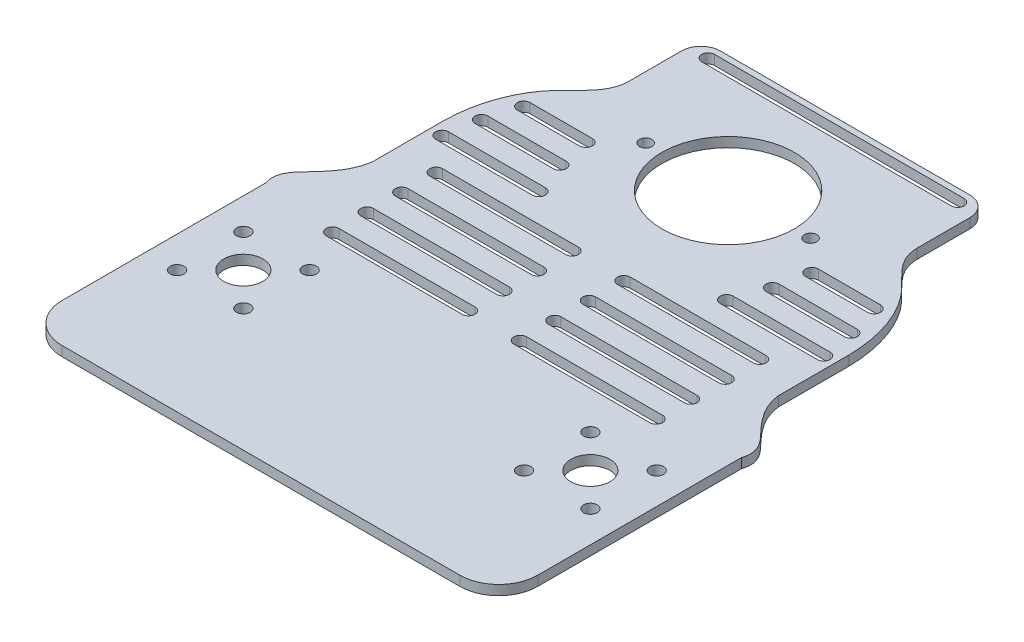
SolidWorks part; units mm, degrees
ref_plane "前视基准面" through (0, 0, 0) normal (0, 0, 1) x (1, 0, 0)
ref_plane "上视基准面" through (0, 0, 0) normal (0, 1, 0) x (1, 0, 0)
ref_plane "右视基准面" through (0, 0, 0) normal (1, 0, 0) x (0, 0, -1)
other "Configuration Table"
sketch "草图1" plane through (0, 0, 0) normal (0, 1, 0) x (1, 0, 0)
  line L0 (0, 1167.4393) -> (0, 111.0115) construction
  line L1 (-53, -10.25) -> (14.9555, -10.25) construction
  line L2 (61, 0) -> (-61, 0) construction
  line L3 (0, 0) -> (0, -39.9914)
  line L4 (51, -39.9914) -> (-51, -39.9914)
  line L5 (-61, 0) -> (-61, -29.9914)
  line L6 (-61, -14.25) -> (61, -14.25) construction
  line L7 (-61, 14.25) -> (61, 14.25) construction
  line L8 (-61, 0) -> (61, 0)
  line L9 (-61, 0) -> (-61, 22.2777)
  line L11 (0, 0) -> (0, -1.9218)
  line L12 (-36, -39.9914) -> (36, -39.9914)
  line L13 (-36, -39.9914) -> (-36, -44.7317)
  line L14 (-36, -44.7317) -> (36, -44.7317)
  line L15 (0, -39.9914) -> (0, -44.7317)
  line L16 (-53, 10.25) -> (-36, 10.25) construction
  line L17 (-53, 10.25) -> (-61, 10.25) construction
  line L18 (-36, 10.25) -> (36, 10.25) construction
  line L19 (-41.5, 19.8859) -> (-6.6294, 19.8859) construction
  line L20 (-41.5, 21.5217) -> (-6.6294, 21.5217)
  line L21 (-41.5, 18.25) -> (-6.6294, 18.25)
  line L22 (-41.5, 28.7359) -> (-6.6294, 28.7359) construction
  line L26 (0, -1.9218) -> (0, 98.1302)
  line L28 (0, 98.1302) -> (0, -1.9218)
  line L30 (-52, 58.8805) -> (-52, 40.7159)
  line L31 (-41.5, 30.3717) -> (-6.6294, 30.3717)
  line L32 (-41.5, 27.1) -> (-6.6294, 27.1)
  line L33 (-41.5, 37.5859) -> (-6.6294, 37.5859) construction
  line L34 (-41.5, 39.2217) -> (-6.6294, 39.2217)
  line L35 (-41.5, 35.95) -> (-6.6294, 35.95)
  line L36 (-41.5, 46.4359) -> (-6.6294, 46.4359) construction
  line L37 (-41.5, 48.0717) -> (-6.6294, 48.0717)
  line L38 (-41.5, 44.8) -> (-6.6294, 44.8)
  line L39 (-24.0647, 72.3323) -> (24.0647, 72.3323) construction
  line L42 (-24.0647, 72.3323) -> (-49.2447, 72.3323) construction
  line L48 (22, 121.0115) -> (-22, 121.0115) construction
  line L50 (0, 98.1302) -> (0, 96.8219)
  line L52 (-37, 91.2941) -> (-37, 104.8452)
  line L55 (32, 109.8452) -> (-32, 109.8452)
  line L59 (0, 0) -> (0, 79.8219)
  line L60 (0, 96.8219) -> (0, -57.2122) construction
  line L70 (-51.5955, 63.9331) -> (51.5955, 63.9331) construction
  line L71 (-52, 55.3812) -> (52, 55.3812) construction
  line L72 (-48.9314, 55.3812) -> (-24.0647, 55.3812) construction
  line L73 (-48.9314, 57.0312) -> (-24.0647, 57.0312)
  line L74 (-48.9314, 53.7312) -> (-24.0647, 53.7312)
  line L75 (-47.365, 63.9331) -> (-27.2748, 63.9331) construction
  line L76 (-47.365, 65.5831) -> (-27.2748, 65.5831)
  line L77 (-47.365, 62.2831) -> (-27.2748, 62.2831)
  line L78 (-44.9325, 72.3323) -> (-28.979, 72.3323) construction
  line L79 (-44.9325, 73.9823) -> (-28.979, 73.9823)
  line L80 (-44.9325, 70.6823) -> (-28.979, 70.6823)
  line L81 (1.339, 106.9185) -> (-1.75, 106.9185) construction
  line L84 (24.0647, 72.3323) -> (49.2447, 72.3323) construction
  line L85 (53, 10.25) -> (61, 10.25) construction
  line L86 (53, 10.25) -> (36, 10.25) construction
  line L88 (37, 91.2941) -> (37, 104.8452)
  line L89 (52, 58.8805) -> (52, 40.7159)
  line L90 (36, -39.9914) -> (36, -44.7317)
  line L91 (61, 0) -> (61, 22.2777)
  line L92 (61, 0) -> (61, -29.9914)
  line L93 (0, 106.9185) -> (1.75, 106.9185) construction
  line L96 (44.9325, 72.3323) -> (28.979, 72.3323) construction
  line L97 (44.9325, 73.9823) -> (28.979, 73.9823)
  line L98 (44.9325, 70.6823) -> (28.979, 70.6823)
  line L99 (47.365, 63.9331) -> (27.2748, 63.9331) construction
  line L100 (47.365, 65.5831) -> (27.2748, 65.5831)
  line L101 (47.365, 62.2831) -> (27.2748, 62.2831)
  line L102 (48.9314, 55.3812) -> (24.0647, 55.3812) construction
  line L103 (48.9314, 57.0312) -> (24.0647, 57.0312)
  line L104 (48.9314, 53.7312) -> (24.0647, 53.7312)
  line L105 (41.5, 46.4359) -> (6.6294, 46.4359) construction
  line L106 (41.5, 48.0717) -> (6.6294, 48.0717)
  line L107 (41.5, 44.8) -> (6.6294, 44.8)
  line L108 (41.5, 37.5859) -> (6.6294, 37.5859) construction
  line L109 (41.5, 39.2217) -> (6.6294, 39.2217)
  line L110 (41.5, 35.95) -> (6.6294, 35.95)
  line L111 (41.5, 28.7359) -> (6.6294, 28.7359) construction
  line L112 (41.5, 30.3717) -> (6.6294, 30.3717)
  line L113 (41.5, 27.1) -> (6.6294, 27.1)
  line L114 (41.5, 19.8859) -> (6.6294, 19.8859) construction
  line L115 (41.5, 21.5217) -> (6.6294, 21.5217)
  line L116 (41.5, 18.25) -> (6.6294, 18.25)
  line L117 (0, 105.1685) -> (0, 98.1302)
  line L118 (-32, 106.6878) -> (32, 106.6878) construction
  line L119 (-32, 108.3378) -> (32, 108.3378)
  line L120 (-32, 105.0378) -> (32, 105.0378)
  line L121 (61, 0) -> (61, -29.9914)
  line L123 (-41.5, 64.1359) -> (-6.6294, 64.1359) construction
  line L124 (-41.5, 65.7717) -> (-6.6294, 65.7717) [skipped]
  line L125 (-41.5, 62.5) -> (-6.6294, 62.5) [skipped]
  line L126 (-41.5, 72.9859) -> (-6.6294, 72.9859) construction
  line L127 (-41.5, 74.6217) -> (-6.6294, 74.6217) [skipped]
  line L128 (-41.5, 71.35) -> (-6.6294, 71.35) [skipped]
  line L129 (-41.5, 55.2859) -> (-6.6294, 55.2859) construction
  line L130 (-41.5, 56.9217) -> (-6.6294, 56.9217) [skipped]
  line L131 (-41.5, 53.65) -> (-6.6294, 53.65) [skipped]
  line L132 (-41.5, 64.1359) -> (-6.6294, 64.1359) construction
  line L133 (-41.5, 65.7717) -> (-6.6294, 65.7717) [skipped]
  line L134 (-41.5, 62.5) -> (-6.6294, 62.5) [skipped]
  line L135 (-41.5, 72.9859) -> (-6.6294, 72.9859) construction
  line L136 (-41.5, 74.6217) -> (-6.6294, 74.6217) [skipped]
  line L137 (-41.5, 71.35) -> (-6.6294, 71.35) [skipped]
  line L138 (-41.5, 55.2859) -> (-6.6294, 55.2859) construction
  line L139 (-41.5, 56.9217) -> (-6.6294, 56.9217) [skipped]
  line L140 (-41.5, 53.65) -> (-6.6294, 53.65) [skipped]
  circle A0 centre (-36, -8.5) radius 1.75
  circle A1 centre (-53, -8.5) radius 1.75
  circle A2 centre (-53, 8.5) radius 1.75
  circle A3 centre (-36, 8.5) radius 1.75
  circle A4 centre (-44.5, 0) radius 5
  arc A6 (-41.5, 21.5217) -> (-41.5, 18.25) centre (-41.5, 19.8859) ccw
  arc A7 (-6.6294, 18.25) -> (-6.6294, 21.5217) centre (-6.6294, 19.8859) ccw
  arc A8 (-51, -39.9914) -> (-61, -29.9914) centre (-51, -29.9914) cw
  arc A9 (-41.5, 30.3717) -> (-41.5, 27.1) centre (-41.5, 28.7359) ccw
  arc A10 (-6.6294, 27.1) -> (-6.6294, 30.3717) centre (-6.6294, 28.7359) ccw
  arc A11 (-41.5, 39.2217) -> (-41.5, 35.95) centre (-41.5, 37.5859) ccw
  arc A12 (-6.6294, 35.95) -> (-6.6294, 39.2217) centre (-6.6294, 37.5859) ccw
  arc A13 (-41.5, 48.0717) -> (-41.5, 44.8) centre (-41.5, 46.4359) ccw
  arc A14 (-6.6294, 44.8) -> (-6.6294, 48.0717) centre (-6.6294, 46.4359) ccw
  circle A21 centre (-21.1455, 79.8219) radius 1.6
  arc A26 (-32, 109.8452) -> (-37, 104.8452) centre (-32, 104.8452) ccw
  circle A27 centre (0, 79.8219) radius 17
  arc A34 (-9.58, 105.1685) -> (-1.7491, 106.862) centre (0, 79.8219) ccw construction
  arc A35 (-48.9314, 57.0312) -> (-48.9314, 53.7312) centre (-48.9314, 55.3812) ccw
  arc A36 (-24.0647, 53.7312) -> (-24.0647, 57.0312) centre (-24.0647, 55.3812) ccw
  arc A37 (-47.365, 65.5831) -> (-47.365, 62.2831) centre (-47.365, 63.9331) ccw
  arc A38 (-27.2748, 62.2831) -> (-27.2748, 65.5831) centre (-27.2748, 63.9331) ccw
  arc A39 (-44.9325, 73.9823) -> (-44.9325, 70.6823) centre (-44.9325, 72.3323) ccw
  arc A40 (-28.979, 70.6823) -> (-28.979, 73.9823) centre (-28.979, 72.3323) ccw
  arc A41 (1.7491, 106.862) -> (1.75, 106.9185) centre (0, 106.9185) ccw
  arc A43 (32, 109.8452) -> (37, 104.8452) centre (32, 104.8452) cw
  circle A44 centre (21.1455, 79.8219) radius 1.6
  arc A45 (51, -39.9914) -> (61, -29.9914) centre (51, -29.9914) ccw
  circle A46 centre (44.5, 0) radius 5
  circle A47 centre (36, 8.5) radius 1.75
  circle A48 centre (53, 8.5) radius 1.75
  circle A49 centre (53, -8.5) radius 1.75
  circle A50 centre (36, -8.5) radius 1.75
  arc A51 (-1.7491, 106.862) -> (-1.75, 106.9185) centre (0, 106.9185) cw
  arc A53 (44.9325, 73.9823) -> (44.9325, 70.6823) centre (44.9325, 72.3323) cw
  arc A54 (28.979, 70.6823) -> (28.979, 73.9823) centre (28.979, 72.3323) cw
  arc A55 (47.365, 65.5831) -> (47.365, 62.2831) centre (47.365, 63.9331) cw
  arc A56 (27.2748, 62.2831) -> (27.2748, 65.5831) centre (27.2748, 63.9331) cw
  arc A57 (48.9314, 57.0312) -> (48.9314, 53.7312) centre (48.9314, 55.3812) cw
  arc A58 (24.0647, 53.7312) -> (24.0647, 57.0312) centre (24.0647, 55.3812) cw
  arc A59 (41.5, 48.0717) -> (41.5, 44.8) centre (41.5, 46.4359) cw
  arc A60 (6.6294, 44.8) -> (6.6294, 48.0717) centre (6.6294, 46.4359) cw
  arc A61 (41.5, 39.2217) -> (41.5, 35.95) centre (41.5, 37.5859) cw
  arc A62 (6.6294, 35.95) -> (6.6294, 39.2217) centre (6.6294, 37.5859) cw
  arc A63 (41.5, 30.3717) -> (41.5, 27.1) centre (41.5, 28.7359) cw
  arc A64 (6.6294, 27.1) -> (6.6294, 30.3717) centre (6.6294, 28.7359) cw
  arc A65 (41.5, 21.5217) -> (41.5, 18.25) centre (41.5, 19.8859) cw
  arc A66 (6.6294, 18.25) -> (6.6294, 21.5217) centre (6.6294, 19.8859) cw
  arc A67 (-32, 108.3378) -> (-32, 105.0378) centre (-32, 106.6878) ccw
  arc A68 (32, 105.0378) -> (32, 108.3378) centre (32, 106.6878) ccw
  arc A69 (-9.58, 105.1685) -> (-1.75, 106.9185) centre (0.4785, 78.5557) cw construction
  arc A77 (-41.5, 65.7717) -> (-41.5, 62.5) centre (-41.5, 64.1359) ccw [skipped]
  arc A78 (-6.6294, 62.5) -> (-6.6294, 65.7717) centre (-6.6294, 64.1359) ccw [skipped]
  arc A79 (-41.5, 74.6217) -> (-41.5, 71.35) centre (-41.5, 72.9859) ccw [skipped]
  arc A80 (-6.6294, 71.35) -> (-6.6294, 74.6217) centre (-6.6294, 72.9859) ccw [skipped]
  arc A81 (-41.5, 56.9217) -> (-41.5, 53.65) centre (-41.5, 55.2859) ccw [skipped]
  arc A82 (-6.6294, 53.65) -> (-6.6294, 56.9217) centre (-6.6294, 55.2859) ccw [skipped]
  spline S0 degree 3 poles (-61, 22.2777) (-62.2938, 26.0793) (-56.6343, 31.1507) (-52.4856, 36.6878) (-52, 40.7159) knots 0 0 0 0 0.462697 1 1 1 1
  spline S1 degree 3 poles (-52, 58.8805) (-51.9064, 66.324) (-48.1792, 79.0568) (-37.0941, 85.9555) (-37, 91.2941) knots 0 0 0 0 0.617361 1 1 1 1
  spline S2 degree 3 poles (52, 58.8805) (51.9064, 66.324) (48.1792, 79.0568) (37.0941, 85.9555) (37, 91.2941) knots 0 0 0 0 0.617361 1 1 1 1
  spline S3 degree 3 poles (61, 22.2777) (62.2938, 26.0793) (56.6343, 31.1507) (52.4856, 36.6878) (52, 40.7159) knots 0 0 0 0 0.462697 1 1 1 1
  point P26 (-57, 10.25)
  point P32 (-24.0647, 19.8859)
  point P39 (0, 48.1042)
  point P45 (0, 0)
  point P52 (-24.0647, 28.7359)
  point P60 (-24.0647, 37.5859)
  point P67 (-24.0647, 46.4359)
  point P74 (-24.0647, 55.3812)
  point P81 (-24.0647, 63.9331)
  point P85 (-24.0647, 55.2859)
  point P88 (-24.0647, 72.3323)
  point P89 (-24.0647, 64.1359)
  point P104 (-11, 121.0115)
  point P113 (-36.498, 55.3812)
  point P114 (-24.0647, 72.9859)
  point P127 (-37.3199, 63.9331)
  point P134 (-36.9557, 72.3323)
  point P141 (-16.2144, 106.9185)
  point P145 (0, 106.6878)
  point P150 (0, 55.3812)
  point P151 (0, 63.9331)
  point P152 (0, 121.0115)
  point P154 (0, 72.3323)
  point P155 (0, 10.25)
  point P158 (0, 14.25)
  point P159 (0, -14.25)
  point P193 (16.2144, 106.9185)
  point P200 (36.9557, 72.3323)
  point P207 (37.3199, 63.9331)
  point P214 (36.498, 55.3812)
  point P219 (11, 121.0115)
  point P220 (24.0647, 72.3323)
  point P221 (24.0647, 63.9331)
  point P222 (24.0647, 55.3812)
  point P225 (24.0647, 46.4359)
  point P232 (24.0647, 37.5859)
  point P239 (24.0647, 28.7359)
  point P246 (24.0647, 19.8859)
  point P258 (-24.0647, 64.1359)
  point P265 (-24.0647, 72.9859)
  point P272 (-24.0647, 55.2859)
  point P279 (-24.0647, 64.1359)
  point P286 (-24.0647, 72.9859)
  point P293 (-24.0647, 55.2859)
  dimension "D1" = 3.5
  dimension "D2" = 36
  dimension "D3" = 2
  dimension "D4" = 2
  dimension "D5" = 4
  dimension "D6" = 17
  dimension "D9" = 4
  dimension "D10" = 41.5
  dimension "D11" = 4
  dimension "D13" = 10
  dimension "D16" = 79.8219
  dimension "D17" = 106.9185
  dimension "D18" = 5
  dimension "D19" = 121.0115
  dimension "D7" = 25
  dimension "D8" = 25.7414
  dimension "D12" = 52
  dimension "D15" = 37
  dimension "D14" = 7
extrude "凸台-拉伸1" add sketch "草图1" along normal blind 2.5
sketch3d "3D草图1"
  line L0 (51, 2.5, 39.9914) -> (-51, 2.5, 39.9914) construction
  line L2 (0, 2.5, 39.9914) -> (-30, 2.5, 39.9914)
  line L10 (0, 2.5, 39.9914) -> (30, 2.5, 39.9914)
  line L11 (-30, 2.5, 39.9914) -> (30.0436, 2.5, 39.9914)
